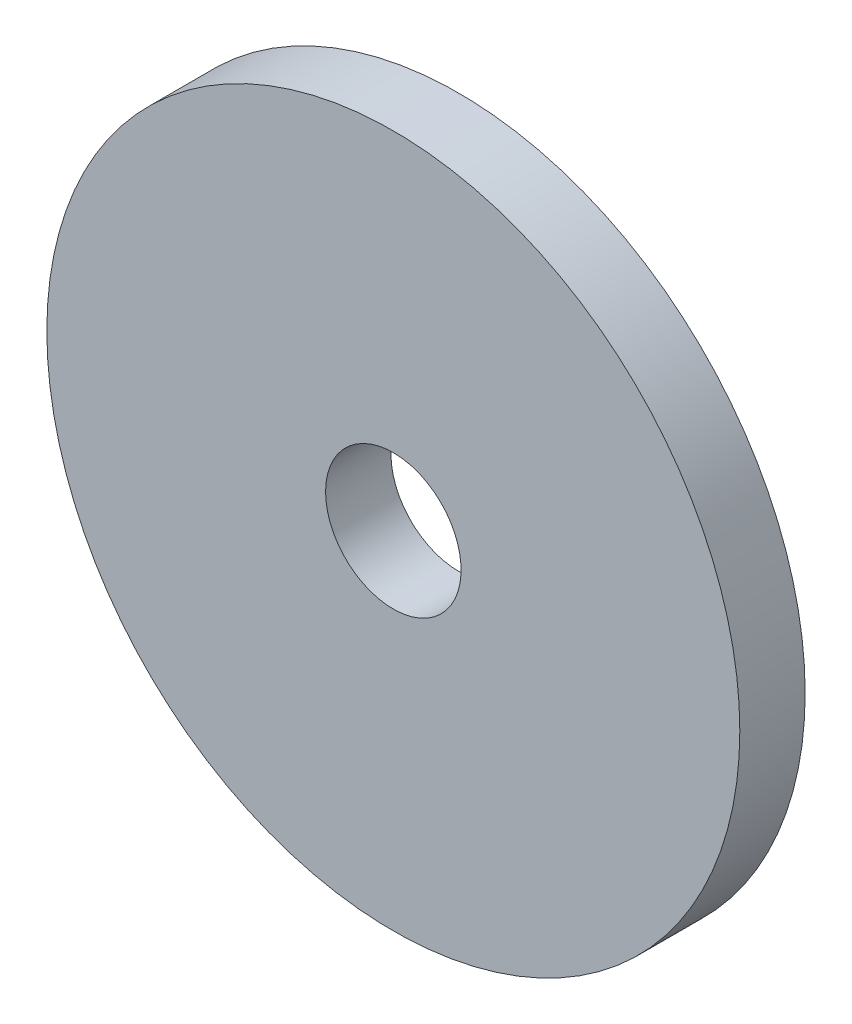
SolidWorks part; units mm, degrees
ref_plane "Front Plane" through (0, 0, 0) normal (0, 0, 1) x (1, 0, 0)
ref_plane "Top Plane" through (0, 0, 0) normal (0, 1, 0) x (1, 0, 0)
ref_plane "Right Plane" through (0, 0, 0) normal (1, 0, 0) x (0, 0, -1)
sketch "Baseplate" plane through (0, 0, 0) normal (0, 0, 1) x (1, 0, 0)
  circle A0 centre (0, 0) radius 101
  circle A2 centre (0, 0) radius 19.747
extrude "Boss-Extrude1" add sketch "Baseplate" along normal blind 19.05
